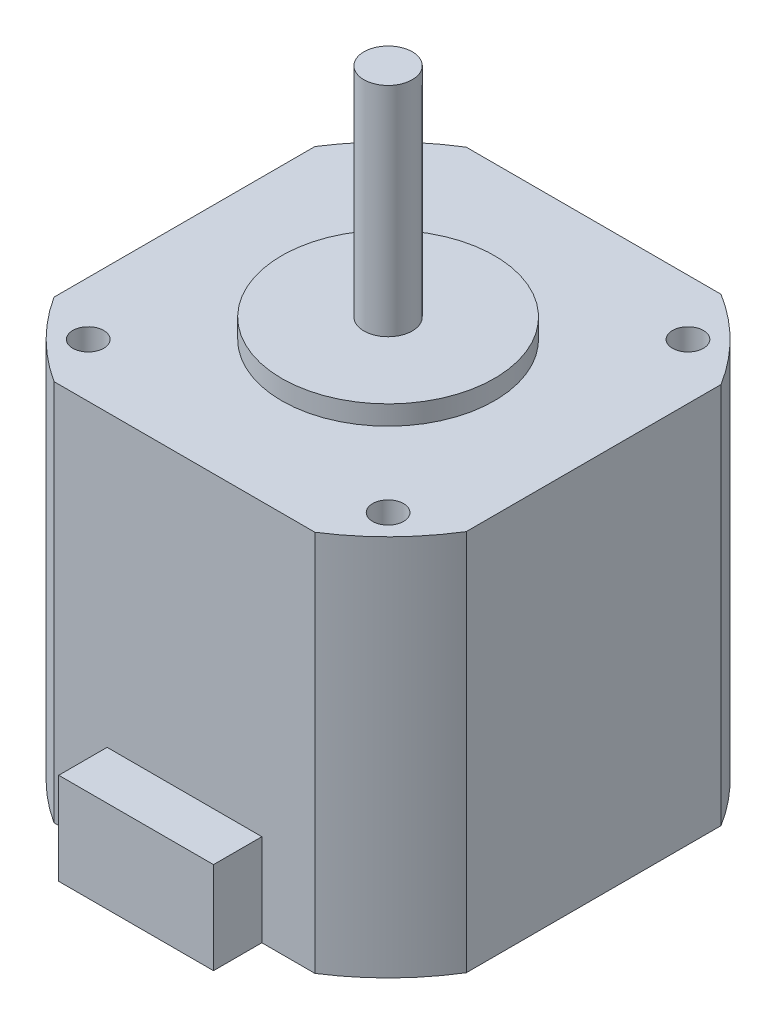
SolidWorks part; units mm, degrees
ref_plane "前视基准面" through (0, 0, 0) normal (0, 0, 1) x (1, 0, 0)
ref_plane "上视基准面" through (0, 0, 0) normal (0, 1, 0) x (1, 0, 0)
ref_plane "右视基准面" through (0, 0, 0) normal (1, 0, 0) x (0, 0, -1)
other "Configuration Table"
sketch "草图1" plane through (0, 0, 0) normal (0, 1, 0) x (1, 0, 0)
  line L1 (0, 0) -> (42.3, 0)
  line L2 (0, 0) -> (0, 42.3)
  line L3 (0, 42.3) -> (42.3, 42.3)
  line L4 (42.3, 0) -> (42.3, 42.3)
  circle A0 centre (21.05, 21.05) radius 25
  dimension "D3" = 50
  dimension "D1" = 42.3
  dimension "D2" = 42.3
  dimension "D4" = 21.25
extrude "凸台-拉伸1" add sketch "草图1" along normal blind 39.5 contours L1 A0 L4 L3 L2
sketch "草图2" plane through (0, 39.5, 0) normal (0, 1, 0) x (1, 0, 0)
  line L0 (3.5055, 38.8598) -> (38.5945, 3.2402) construction
  line L1 (3.3723, 3.3723) -> (38.7277, 38.7277) construction
  circle A4 centre (21.05, 21.05) radius 11
  dimension "D1" = 22
extrude "凸台-拉伸2" add sketch "草图2" along normal blind 2
sketch "草图3" plane through (0, 41.5, 0) normal (0, 1, 0) x (1, 0, 0)
  circle A0 centre (21.05, 21.05) radius 2.5
extrude "凸台-拉伸3" add sketch "草图3" along normal blind 22.5
sketch "草图4" plane through (0, 0, 0) normal (0, 1, 0) x (1, 0, 0)
  line L0 (7.5631, 0) -> (34.5369, 0) construction
  line L1 (13.05, 0) -> (29.05, 0)
  line L2 (13.05, 0) -> (13.05, -5)
  line L3 (13.05, -5) -> (29.05, -5)
  line L4 (29.05, 0) -> (29.05, -5)
  line L5 (21.05, 42.3) -> (21.05, -4.006) construction
  dimension "D1" = 16
  dimension "D2" = 8
  dimension "D3" = 5
extrude "凸台-拉伸4" add sketch "草图4" along normal blind 9.5
sketch "草图5" plane through (0, 39.5, 0) normal (0, 1, 0) x (1, 0, 0)
  line L0 (0, 21.05) -> (42.3, 21.05) construction
  line L3 (21.05, 42.3) -> (21.05, 0) construction
  circle A0 centre (5.55, 36.55) radius 1.6
  circle A1 centre (36.55, 36.55) radius 1.6
  circle A2 centre (36.55, 5.55) radius 1.6
  circle A3 centre (5.55, 5.55) radius 1.6
  dimension "D1" = 3.2
  dimension "D2" = 15.5
  dimension "D3" = 15.5
extrude "切除-拉伸1" cut sketch "草图5" against normal blind 5
